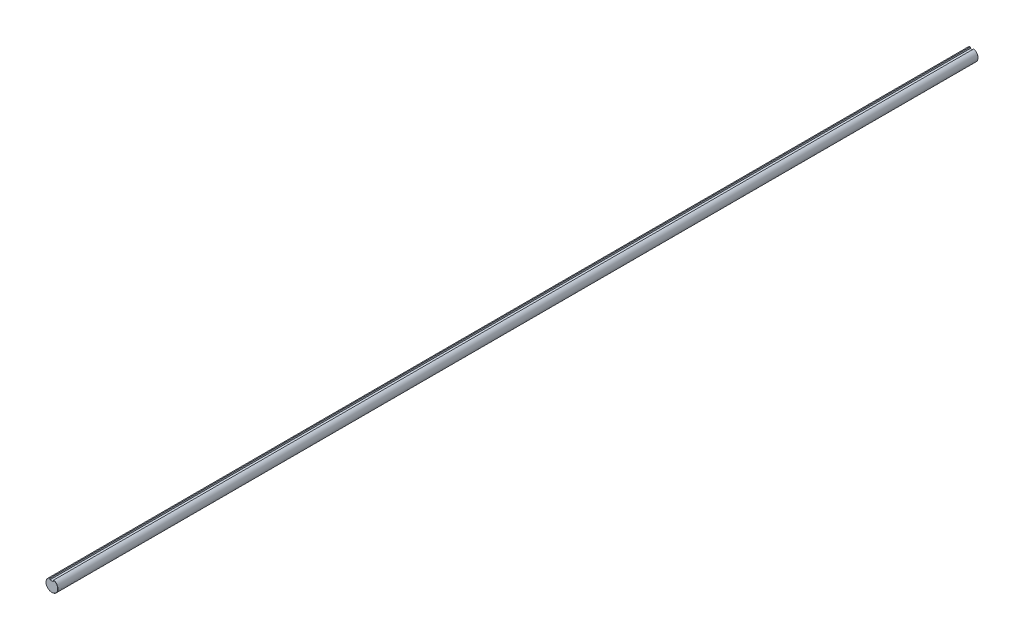
SolidWorks part; units mm, degrees
ref_plane "Front Plane" through (0, 0, 0) normal (0, 0, 1) x (1, 0, 0)
ref_plane "Top Plane" through (0, 0, 0) normal (0, 1, 0) x (1, 0, 0)
ref_plane "Right Plane" through (0, 0, 0) normal (1, 0, 0) x (0, 0, -1)
sketch "Sketch1" plane through (0, 0, 0) normal (1, 0, 0) x (0, 0, -1)
  line L0 (0, 0) -> (0, 3.9687) construction
  line L1 (-304.8, 3.9687) -> (304.8, 3.9688)
  line L2 (-304.8, 3.9687) -> (-304.8, -3.9688)
  line L3 (-304.8, -3.9688) -> (304.8, -3.9687)
  line L4 (304.8, 3.9688) -> (304.8, -3.9687)
  line L5 (-304.8, 3.9687) -> (304.8, -3.9687) construction
  line L6 (-304.8, -3.9688) -> (304.8, 3.9688) construction
  line L7 (0, 0) -> (0, -3.9688) construction
  line L8 (304.8, 3.9688) -> (-304.8, 3.9687) construction
  point P0 (0, 0)
  point P8 (-295.6719, 3.9687)
  point P10 (295.6719, 3.9687)
  point P11 (-292.6292, -3.9687)
  point P12 (294.2598, -3.9687)
  point P15 (0, 3.9687)
  dimension "Diameter" = 7.9375
  dimension "Length" = 609.6
  dimension "D1" = 9.1281
  dimension "D2" = 9.1281
  dimension "D3" = 12.1708
  dimension "D4" = 10.5402
  dimension "Key Length" = 609.6
sketch "Sketch2" plane through (0, 0, 0) normal (0, 0, 1) x (1, 0, 0)
  line L0 (0, 0) -> (0, 3.9687) construction
  line L2 (1.1938, 2.7749) -> (-1.1938, 2.7749)
  line L3 (1.1938, 2.7749) -> (1.1938, 3.9687)
  line L4 (1.1938, 3.9687) -> (-1.1938, 3.9687)
  line L5 (-1.1938, 2.7749) -> (-1.1938, 3.9687)
  line L6 (1.1938, 2.7749) -> (-1.1938, 3.9687) construction
  line L7 (1.1938, 3.9687) -> (-1.1938, 2.7749) construction
  circle A0 centre (0, 0) radius 3.9687
  point P3 (0, 3.3718)
  dimension "Keyway Width" = 2.3876
  dimension "Keyway Depth" = 1.1938
sketch "Sketch3" plane through (0, 0, 0) normal (0, 0, 1) x (1, 0, 0)
  line L1 (-1.1938, 2.7749) -> (-1.1938, 3.9687) construction
  line L2 (1.1938, 2.7749) -> (-1.1938, 2.7749) construction
  line L3 (1.1938, 2.7749) -> (1.1938, 3.9687) construction
  line L5 (-1.1938, 2.7749) -> (-1.1938, 3.7849)
  line L6 (1.1938, 2.7749) -> (-1.1938, 2.7749)
  line L7 (1.1938, 2.7749) -> (1.1938, 3.7849)
  arc A1 (-1.1938, 3.7849) -> (1.1938, 3.7849) centre (0, 0) ccw
  circle A2 centre (0, 0) radius 3.9687 construction
extrude "Boss-Extrude1" add sketch "Sketch3" along normal up to vertex (304.8 mm away) and the other way up to vertex (304.8 mm away) up to point (0, 3.9687, 304.8) other way up to point (0, 3.9688, -304.8)
chamfer "Chamfer1" distance 0.0794 angle 45 2 edges at (0, -3.9687, 304.8) (0, -3.9687, -304.8)
equation "\"D2@Sketch1\"=1.15*\"Diameter@Sketch1\""
equation "\"D1@Sketch1\"=\"D2@Sketch1\""
equation "\"D3@Sketch1\"=\"D2@Sketch1\"*4/3"
equation "\"D4@Sketch1\"=\"D2@Sketch1\"/(tan(.5236*180/pi)*2)*4/3"
equation "\"D1@Chamfer1\"=\"Diameter@Sketch1\"*.01"
equation "\"Key Length@Sketch1\"=\"Length@Sketch1\""
